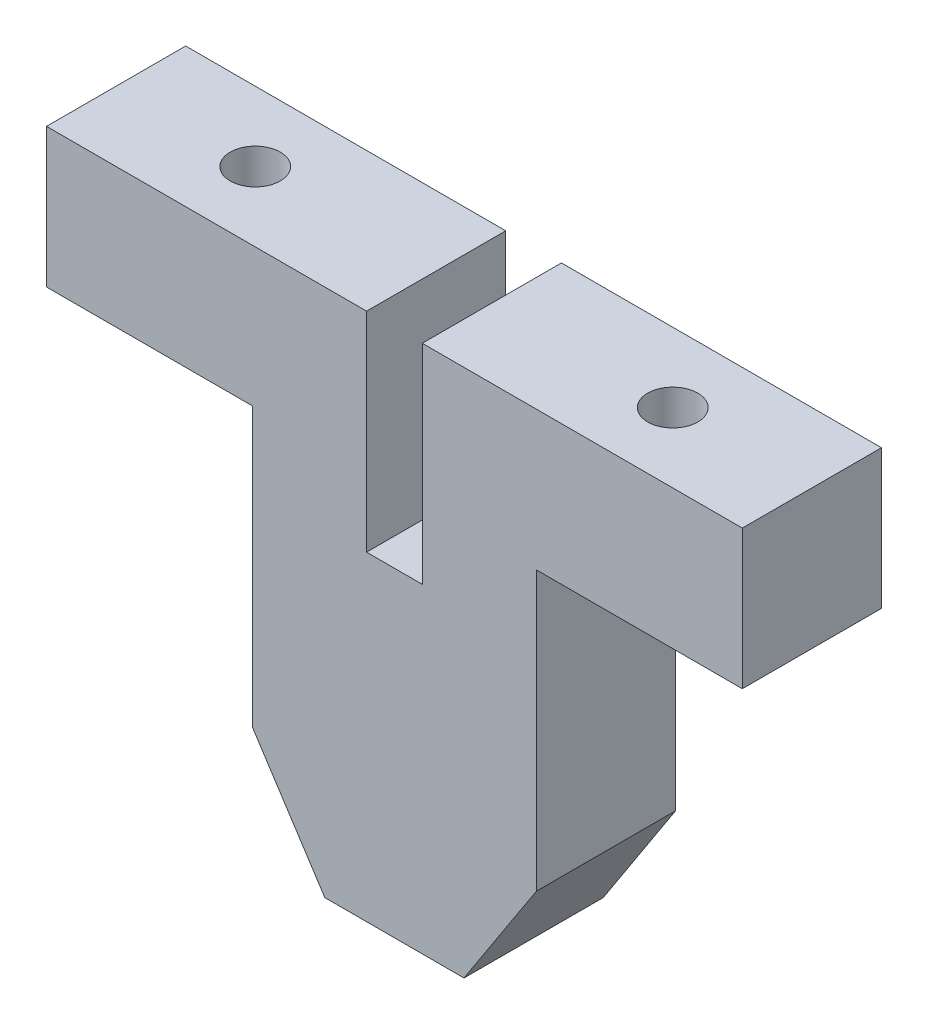
SolidWorks part; units mm, degrees
ref_plane "Front Plane" through (0, 0, 0) normal (0, 0, 1) x (1, 0, 0)
ref_plane "Top Plane" through (0, 0, 0) normal (0, 1, 0) x (1, 0, 0)
ref_plane "Right Plane" through (0, 0, 0) normal (1, 0, 0) x (0, 0, -1)
sketch "Sketch1" plane through (0, 0, 0) normal (0, 0, 1) x (1, 0, 0)
  line L0 (0, 0) -> (0, 38)
  line L1 (0, 38) -> (50, 38)
  line L2 (50, 38) -> (50, 0)
  line L3 (50, 0) -> (0, 0)
  line L4 (25, 38) -> (25, 0) construction
  dimension "D1" = 50
  dimension "D2" = 50
  dimension "D3" = 38
extrude "Boss-Extrude1" add sketch "Sketch1" along normal blind 10
sketch "Sketch2" plane through (0, 38, 0) normal (0, 1, 0) x (1, 0, 0)
  line L0 (10, -5) -> (40, -5) construction
  line L1 (25, -5) -> (25, 0) construction
  line L4 (50, 0) -> (0, 0) construction
  line L5 (50, -10) -> (0, -10) construction
  circle A0 centre (10, -5) radius 1.8
  circle A1 centre (40, -5) radius 1.8
  dimension "D3" = 30
  dimension "D4" = 3.6
  dimension "D5" = 3.6
  dimension "D1" = 5
  dimension "D2" = 5
extrude "Cut-Extrude1" cut sketch "Sketch2" against normal through all
sketch "Sketch3" plane through (0, 0, 10) normal (0, 0, 1) x (1, 0, 0)
  line L0 (50, 38) -> (0, 38) construction
  line L1 (23, 38) -> (27, 38)
  line L2 (23, 38) -> (23, 23)
  line L3 (23, 23) -> (27, 23)
  line L4 (27, 38) -> (27, 23)
  line L5 (0, 38) -> (23, 23) construction
  line L6 (27, 23) -> (50, 38) construction
  dimension "D1" = 4
  dimension "D2" = 15
extrude "Cut-Extrude2" cut sketch "Sketch3" against normal blind 10
sketch "Sketch4" plane through (0, 0, 10) normal (0, 0, 1) x (1, 0, 0)
  line L0 (0, 28) -> (14.8, 28)
  line L1 (0, 38) -> (0, 0) construction
  line L2 (14.8, 28) -> (14.8, 8)
  line L3 (14.8, 8) -> (20, 0)
  line L4 (0, 0) -> (50, 0) construction
  line L5 (20, 0) -> (30, 0)
  line L6 (30, 0) -> (35.2, 8)
  line L7 (35.2, 8) -> (35.2, 28)
  line L8 (35.2, 28) -> (50, 28)
  line L9 (50, 0) -> (50, 38) construction
  line L10 (50, 28) -> (50, -1)
  line L11 (50, -1) -> (0, -1)
  line L12 (0, -1) -> (0, 28)
  line L13 (23, 38) -> (0, 38) construction
  line L15 (23, 23) -> (27, 23) construction
  line L16 (25, 23) -> (25, 0) construction
  line L17 (14.8, 8) -> (35.2, 8) construction
  line L18 (14.8, 28) -> (35.2, 28) construction
  line L19 (11.8, 0) -> (11.8, 38) construction
  point P18 (25, 8)
  point P19 (0, 0)
  point P22 (25, 23)
  point P25 (20.402, 0)
  dimension "D1" = 1
  dimension "D2" = 10
  dimension "D3" = 3
  dimension "D4" = 15
  dimension "D5" = 10
extrude "Cut-Extrude3" cut sketch "Sketch4" against normal through all
